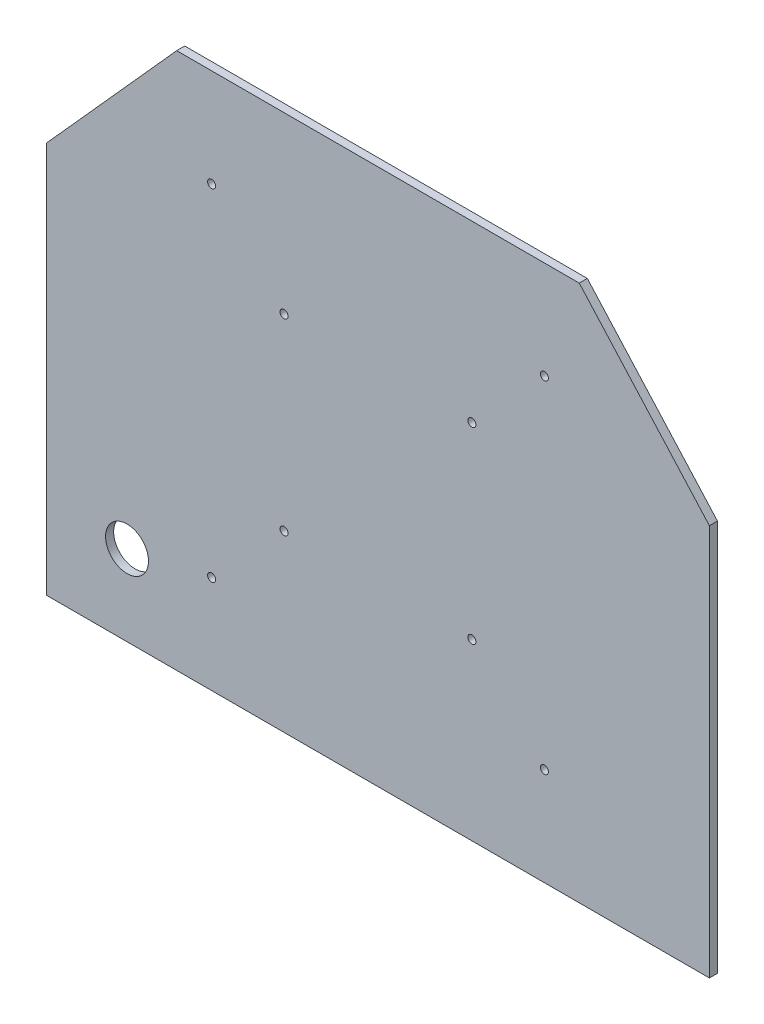
SolidWorks part; units mm, degrees
ref_plane "Plan de face" through (0, 0, 0) normal (0, 0, 1) x (1, 0, 0)
ref_plane "Plan de dessus" through (0, 0, 0) normal (0, 1, 0) x (1, 0, 0)
ref_plane "Plan de droite" through (0, 0, 0) normal (1, 0, 0) x (0, 0, -1)
sketch "Esquisse1" plane through (0, 0, 0) normal (0, 0, 1) x (1, 0, 0)
  line L0 (0, 0) -> (280.2, 0) construction
  line L1 (280.2, 0) -> (280.2, 127.45) construction
  line L2 (280.2, 127.45) -> (215.1, 200) construction
  line L3 (215.1, 200) -> (65.1, 200) construction
  line L4 (65.1, 200) -> (0, 127.45) construction
  line L5 (0, 0) -> (0, 127.45) construction
  line L6 (0, 0) -> (0, 127.45)
  line L7 (0, 127.45) -> (65.1, 200)
  line L8 (65.1, 200) -> (215.1, 200)
  line L9 (215.1, 200) -> (280.2, 127.45)
  line L10 (280.2, 127.45) -> (280.2, 0)
  line L11 (280.2, 0) -> (0, 0)
  point P3 (140.1, 200)
  point P8 (140.1, 0)
  dimension "D1" = 280.2
  dimension "D2" = 200
  dimension "D3" = 127.45
  dimension "D4" = 127.45
  dimension "D5" = 150
extrude "Boss.-Extru.1" add sketch "Esquisse1" along normal blind 3
sketch "Esquisse2" plane through (0, 0, 0) normal (0, 0, -1) x (-1, 0, 0)
  line L1 (-16.6, 252) -> (-16.6, 0) construction
  line L2 (-16.6, 0) -> (-16.6, 145.9694)
  line L3 (-16.6, 0) -> (0, 0)
  line L4 (0, 0) -> (0, 127.45)
  line L5 (0, 127.45) -> (-16.6, 145.9694)
  line L6 (-140.1, 200) -> (-140.1, -18.7191) construction
  line L7 (-215.1, 200) -> (-65.1, 200) construction
  line L8 (-280.2, 127.45) -> (-263.6, 145.9694)
  line L9 (-280.2, 0) -> (-280.2, 127.45)
  line L10 (-263.6, 0) -> (-280.2, 0)
  line L11 (-263.6, 0) -> (-263.6, 145.9694)
extrude "Enlèv. mat.-Extru.1" cut sketch "Esquisse2" against normal through all
sketch "Esquisse3" plane through (0, 0, 3) normal (0, 0, 1) x (1, 0, 0)
  line L0 (140.1, 200) -> (140.1, -25.2955) construction
  line L1 (215.1, 200) -> (65.1, 200) construction
  line L2 (215.1, 200) -> (65.1, 200) construction
  circle A0 centre (78.1, 163.5) radius 1.5
  circle A1 centre (78.1, 36.5) radius 1.5
  circle A2 centre (202.1, 36.5) radius 1.5
  circle A3 centre (202.1, 163.5) radius 1.5
  point P14 (0, 0)
  dimension "D1" = 3
  dimension "D2" = 3
  dimension "D4" = 36.5
  dimension "D3" = 127
  dimension "D5" = 62
extrude "Enlèv. mat.-Extru.2" cut sketch "Esquisse3" against normal through all
sketch "Esquisse4" plane through (0, 0, 3) normal (0, 0, 1) x (1, 0, 0)
  line L0 (16.6, 0) -> (263.6, 0) construction
  line L2 (16.6, 145.9497) -> (16.6, 0) construction
  circle A0 centre (46.6, 30) radius 8
  dimension "D1" = 16
  dimension "D2" = 30
  dimension "D3" = 30
extrude "Enlèv. mat.-Extru.3" cut sketch "Esquisse4" against normal through all
sketch "Esquisse5" plane through (0, 0, 3) normal (0, 0, 1) x (1, 0, 0)
  line L0 (140.1, 249.9536) -> (140.1, 47.0182) construction
  line L1 (2.6642, 100) -> (310.5804, 100) construction
  line L2 (215.1, 200) -> (65.1, 200) construction
  circle A0 centre (105.1, 65) radius 1.5
  circle A1 centre (105.1, 135) radius 1.5
  circle A2 centre (175.1, 135) radius 1.5
  circle A3 centre (175.1, 65) radius 1.5
  point P14 (140.1, 200)
  dimension "D1" = 3
  dimension "D2" = 3
  dimension "D3" = 3
  dimension "D4" = 3
  dimension "D5" = 70
  dimension "D6" = 70
  dimension "D7" = 70
  dimension "D8" = 70
  dimension "D9" = 35
  dimension "D10" = 35
  dimension "D11" = 35
  dimension "D12" = 100
extrude "Enlèv. mat.-Extru.4" cut sketch "Esquisse5" against normal through all
